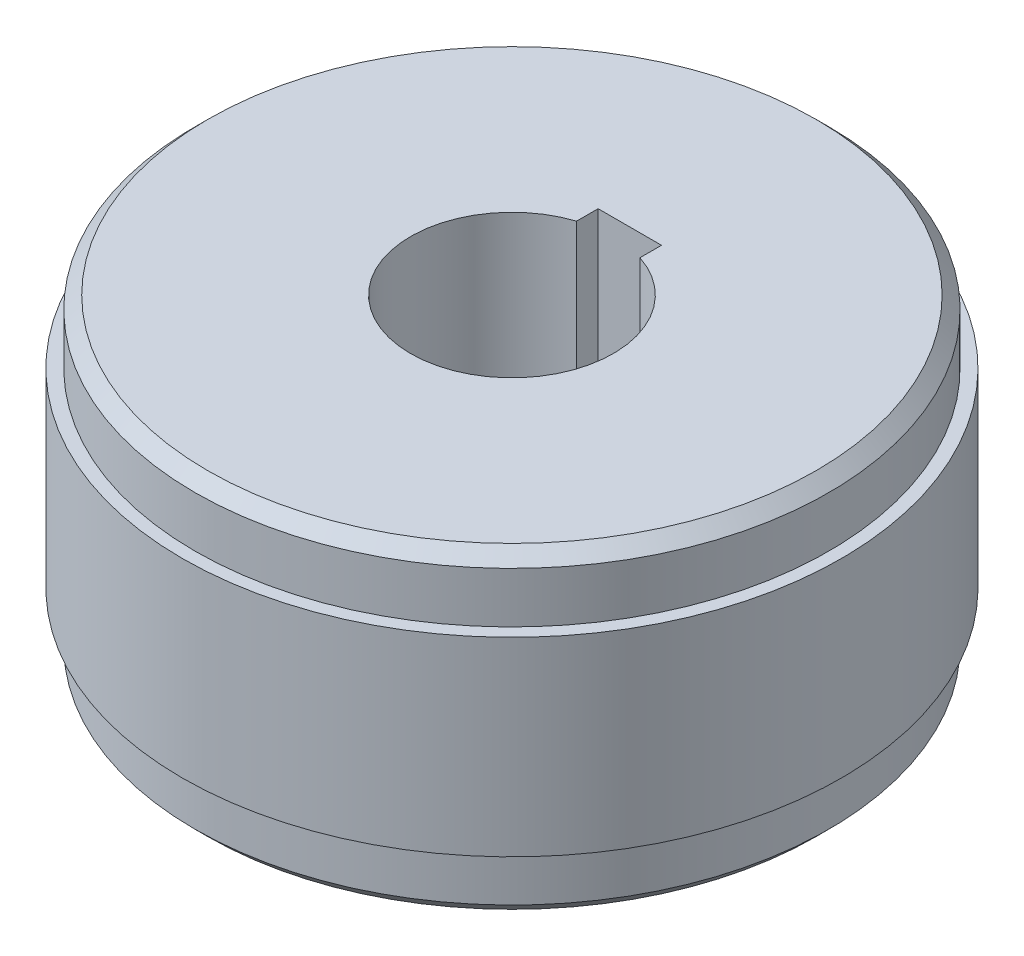
SolidWorks part; units mm, degrees
ref_plane "前视基准面" through (0, 0, 0) normal (0, 0, 1) x (1, 0, 0)
ref_plane "上视基准面" through (0, 0, 0) normal (0, 1, 0) x (1, 0, 0)
ref_plane "右视基准面" through (0, 0, 0) normal (1, 0, 0) x (0, 0, -1)
other "Configuration Table"
sketch "草图1" plane through (0, 0, 0) normal (0, 1, 0) x (1, 0, 0)
  line L0 (0, 67.9563) -> (0, -89.9273) construction
  line L1 (-2.5, 7.5993) -> (-2.5, 9.3)
  line L2 (-2.5, 9.3) -> (2.5, 9.3)
  line L3 (2.5, 9.3) -> (2.5, 7.5993)
  circle A0 centre (0, 0) radius 25
  arc A2 (-2.5, 7.5993) -> (2.5, 7.5993) centre (0, 0) ccw
  dimension "D1" = 5
  dimension "D3" = 50
  dimension "D4" = 8
  dimension "D2" = 9.3
extrude "凸台-拉伸1" add sketch "草图1" along normal mid plane 25
sketch "草图2" plane through (0, 0, 0) normal (0, 1, 0) x (1, 0, 0)
  circle A0 centre (0, 0) radius 24
  circle A1 centre (0, 0) radius 26
  dimension "D1" = 48
  dimension "D2" = 52
extrude "凸台-拉伸2" add sketch "草图2" along normal mid plane 15
chamfer "倒角1" distance 1 angle 45 2 edges at (0, 12.5, 25) (0, -12.5, 25)
